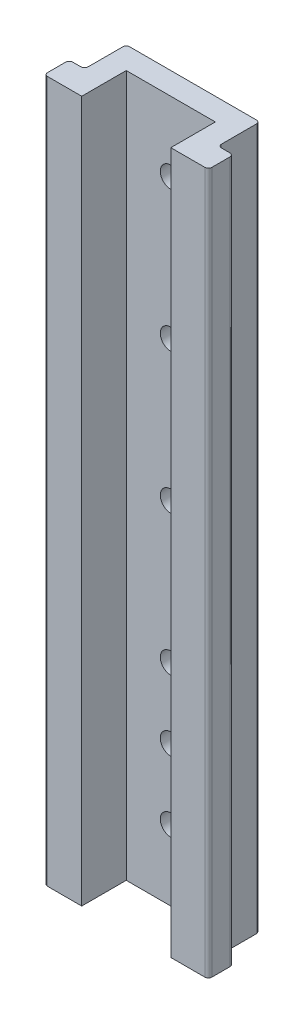
SolidWorks part; units mm, degrees
ref_plane "Front Plane" through (0, 0, 0) normal (0, 0, 1) x (1, 0, 0)
ref_plane "Top Plane" through (0, 0, 0) normal (0, 1, 0) x (1, 0, 0)
ref_plane "Right Plane" through (0, 0, 0) normal (1, 0, 0) x (0, 0, -1)
sketch "Sketch1" plane through (0, 0, 0) normal (0, 1, 0) x (1, 0, 0)
  line L0 (11.2078, 0) -> (6.35, 0)
  line L1 (6.35, 0) -> (6.35, 6.35)
  line L2 (6.35, 6.35) -> (-6.35, 6.35)
  line L3 (0, 6.35) -> (0, 9.525) construction
  line L4 (-9.025, 9.525) -> (9.025, 9.525)
  line L5 (9.525, 9.025) -> (9.525, 4.0719)
  line L6 (10.025, 3.5719) -> (11.2078, 3.5719)
  line L7 (11.7078, 3.0719) -> (11.7078, 0.5)
  line L8 (-11.7078, 3.0719) -> (-11.7078, 0.5)
  line L9 (-10.025, 3.5719) -> (-11.2078, 3.5719)
  line L10 (-9.525, 9.025) -> (-9.525, 4.0719)
  line L11 (-6.35, 0) -> (-6.35, 6.35)
  line L12 (-11.2078, 0) -> (-6.35, 0)
  line L13 (-6.35, 6.35) -> (-9.525, 6.35) construction
  arc A0 (11.2078, 0) -> (11.7078, 0.5) centre (11.2078, 0.5) ccw
  arc A1 (11.2078, 3.5719) -> (11.7078, 3.0719) centre (11.2078, 3.0719) cw
  arc A2 (9.525, 4.0719) -> (10.025, 3.5719) centre (10.025, 4.0719) ccw
  arc A3 (9.025, 9.525) -> (9.525, 9.025) centre (9.025, 9.025) cw
  arc A4 (-11.7078, 0.5) -> (-11.2078, 0) centre (-11.2078, 0.5) ccw
  arc A5 (-11.7078, 3.0719) -> (-11.2078, 3.5719) centre (-11.2078, 3.0719) cw
  arc A6 (-10.025, 3.5719) -> (-9.525, 4.0719) centre (-10.025, 4.0719) ccw
  arc A7 (-9.525, 9.025) -> (-9.025, 9.525) centre (-9.025, 9.025) cw
  point P18 (11.7078, 0)
  point P21 (11.7078, 3.5719)
  point P24 (9.525, 3.5719)
  point P27 (9.525, 9.525)
  point P30 (-11.7078, 0)
  point P33 (-11.7078, 3.5719)
  point P36 (-9.525, 3.5719)
  point P39 (-9.525, 9.525)
  dimension "D6" = 0.5
  dimension "D1" = 3.5719
  dimension "D2" = 5.9531
  dimension "D3" = 19.05
  dimension "D4" = 23.4156
  dimension "D5" = 3.175
extrude "Boss-Extrude1" add sketch "Sketch1" along normal blind 100
sketch "Sketch2" plane through (0, 0, -9.525) normal (0, 0, -1) x (-1, 0, 0)
  circle A0 centre (0, 10) radius 1.5
  circle A1 centre (0, 20) radius 1.5
  circle A2 centre (0, 30) radius 1.5
  circle A3 centre (0, 50) radius 1.5
  circle A4 centre (0, 70) radius 1.5
  circle A5 centre (0, 90) radius 1.5
  dimension "D1" = 3
  dimension "D2" = 10
  dimension "D3" = 2
  dimension "D4" = 5
extrude "Cut-Extrude1" cut sketch "Sketch2" against normal up to next
